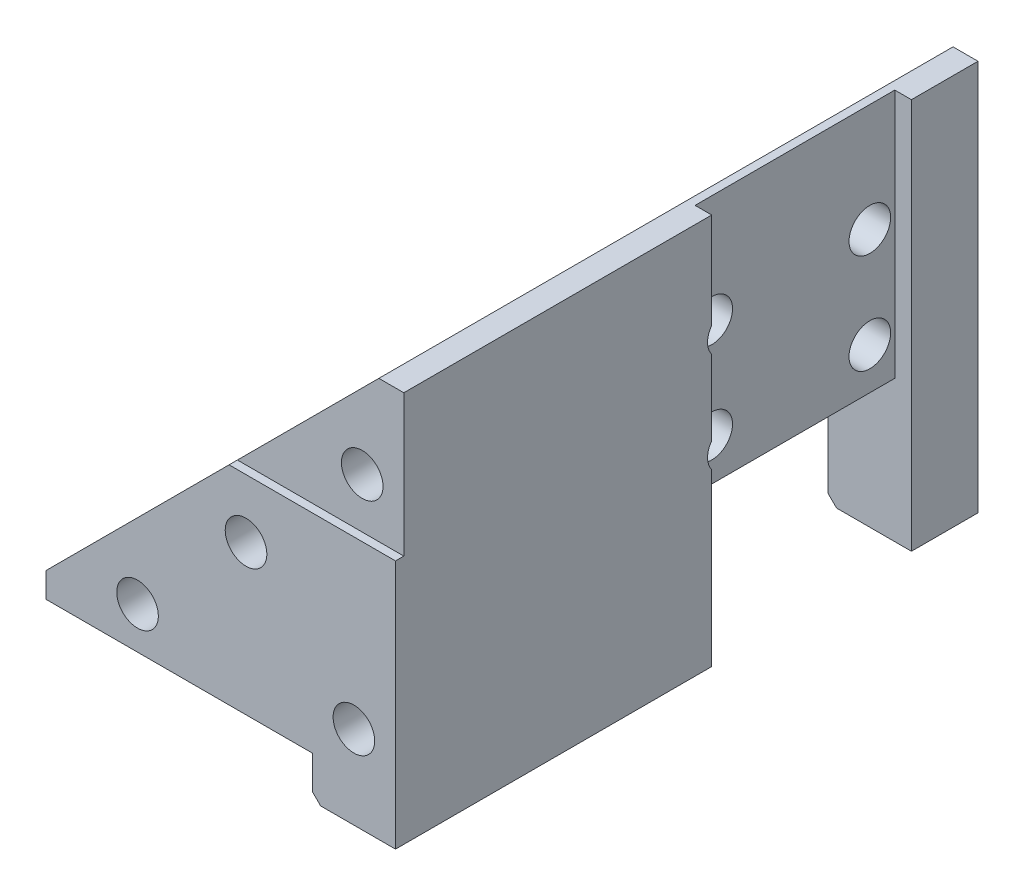
SolidWorks part; units mm, degrees
ref_plane "前视基准面" through (0, 0, 0) normal (0, 0, 1) x (1, 0, 0)
ref_plane "上视基准面" through (0, 0, 0) normal (0, 1, 0) x (1, 0, 0)
ref_plane "右视基准面" through (0, 0, 0) normal (1, 0, 0) x (0, 0, -1)
sketch "草图1" plane through (0, 0, 0) normal (0, 0, 1) x (1, 0, 0)
  line L0 (0, 0) -> (50, 0)
  line L1 (50, 0) -> (50, 50)
  line L3 (50, 50) -> (0, 0)
  dimension "D1" = 45
  dimension "D2" = 50
extrude "拉伸1" add sketch "草图1" along normal blind 70
sketch "草图2" plane through (0, 0, 70) normal (0, 0, 1) x (1, 0, 0)
  line L0 (0, 0) -> (50, 0) construction
  line L1 (40, 0) -> (-5.5322, 0)
  line L2 (40, 0) -> (40, 5)
  line L3 (40, 5) -> (-5.5322, 5)
  line L4 (-5.5322, 0) -> (-5.5322, 5)
  line L5 (50, 0) -> (50, 50) construction
  dimension "D1" = 5
  dimension "D2" = 10
extrude "切除-拉伸1" cut sketch "草图2" against normal through all
sketch "草图3" plane through (0, 5, 0) normal (0, -1, 0) x (1, 0, 0)
  line L0 (5, 0) -> (5, 70) construction
  line L1 (5, 60) -> (40, 60)
  line L2 (5, 60) -> (5, 50)
  line L3 (5, 50) -> (40, 50)
  line L4 (40, 60) -> (40, 50)
  line L5 (40, 0) -> (40, 70) construction
  line L6 (40, 70) -> (5, 70) construction
  line L7 (40, 0) -> (40, 70) construction
  line L8 (5, 40) -> (40, 40)
  line L9 (5, 40) -> (5, -6.8664)
  line L10 (5, -6.8664) -> (40, -6.8664)
  line L11 (40, 40) -> (40, -6.8664)
  dimension "D1" = 10
  dimension "D2" = 10
  dimension "D4" = 10
extrude "切除-拉伸2" cut sketch "草图3" against normal through all
sketch "草图4" plane through (0, 0, 70) normal (0, 0, 1) x (1, 0, 0)
  line L0 (5, 5) -> (8, 5)
  line L1 (40, 5) -> (5, 5) construction
  line L2 (8, 5) -> (8, 8)
  line L3 (50, 50) -> (5, 5) construction
  line L4 (8, 8) -> (5, 5)
  line L5 (50, 0) -> (50, 50) construction
  dimension "D1" = 42
extrude "切除-拉伸3" cut sketch "草图4" against normal through all
sketch "草图9" plane through (0, 0, 70) normal (0, 0, 1) x (1, 0, 0)
  line L0 (45, 36) -> (45, -4.6251) construction
  line L1 (50, 0) -> (50, 50) construction
  line L2 (40, 0) -> (50, 0) construction
  line L3 (50, 25) -> (8.9352, 25) construction
  line L4 (45, 36) -> (19, 10) construction
  line L5 (19, 10) -> (45, 10) construction
  line L6 (50, 50) -> (8, 8) construction
  circle A0 centre (45, 36) radius 2.5
  circle A1 centre (45, 10) radius 2.5
  circle A2 centre (19, 10) radius 2.5
  dimension "D2" = 5
  dimension "D1" = 5
  dimension "D3" = 10
  dimension "D4" = 26
extrude "切除-拉伸7" cut sketch "草图9" against normal up to surface (20 mm away) up to face at (24, 14.5, 50)
sketch "草图6" plane through (0, 0, 70) normal (0, 0, 1) x (1, 0, 0)
  line L0 (45, 36) -> (19, 10) construction
  line L2 (45, 10) -> (32.0363, 22.9637) construction
  circle A0 centre (32.0363, 22.9637) radius 6.5 construction
  dimension "D3" = 13
sketch "草图7" plane through (0, 0, 40) normal (0, 0, -1) x (-1, 0, 0)
  circle A0 centre (-32.0363, 22.9637) radius 2.5
  circle A1 centre (-32.0363, 22.9637) radius 6.5 construction
  dimension "D1" = 5
chamfer "倒角1" distance 1 angle 45 3 edges at (24, 5, 60) (24, 5, 50) (24, 5, 40)
sketch "草图11" plane through (0, 5, 0) normal (0, -1, 0) x (1, 0, 0)
  line L0 (40, 70) -> (8, 70) construction
  line L1 (40, 61) -> (40, 70) construction
  circle A0 centre (34, 65) radius 3.75
  dimension "D1" = 7.5
  dimension "D2" = 5
  dimension "D3" = 6
extrude "切除-拉伸10" cut sketch "草图11" against normal blind 8
sketch "草图13" plane through (0, 0, 70) normal (0, 0, 1) x (1, 0, 0)
  line L0 (50, 50) -> (47, 47)
  line L1 (50, 50) -> (8, 8) construction
  line L2 (47, 47) -> (50, 47)
  line L3 (50, 0) -> (50, 50) construction
  line L4 (50, 47) -> (50, 50)
  dimension "D1" = 3
extrude "切除-拉伸11" cut sketch "草图13" against normal through all
sketch "草图14" plane through (0, 0, 70) normal (0, 0, 1) x (1, 0, 0)
  line L0 (50, 47) -> (47, 47)
  line L1 (47, 47) -> (30, 30)
  line L2 (47, 47) -> (8, 8) construction
  line L3 (30, 30) -> (50, 30)
  line L4 (50, 0) -> (50, 47) construction
  line L5 (50, 30) -> (50, 47)
  dimension "D1" = 17
extrude "切除-拉伸12" cut sketch "草图14" against normal blind 1
sketch "草图15" plane through (40, 0, 0) normal (-1, 0, 0) x (0, 0, 1)
  line L0 (0, 0) -> (70, 0) construction
  line L1 (8, 0) -> (32, 0)
  line L2 (8, 0) -> (8, 17)
  line L3 (8, 17) -> (32, 17)
  line L4 (32, 0) -> (32, 17)
  line L5 (0, 0) -> (0, 40) construction
  dimension "D1" = 17
  dimension "D2" = 8
  dimension "D3" = 24
extrude "切除-拉伸14" cut sketch "草图15" against normal blind 10
sketch "草图16" plane through (40, 0, 0) normal (-1, 0, 0) x (0, 0, 1)
  line L0 (30, 34) -> (11, 34) construction
  line L1 (30, 22) -> (11, 22) construction
  line L2 (30, 34) -> (30, 22) construction
  line L3 (11, 34) -> (11, 22) construction
  line L4 (0, 0) -> (0, 40) construction
  line L5 (0, 0) -> (8, 0) construction
  circle A0 centre (30, 34) radius 2.5
  circle A1 centre (30, 22) radius 2.5
  circle A2 centre (11, 34) radius 2.5
  circle A3 centre (11, 22) radius 2.5
  point P10 (4, 0)
  dimension "D1" = 5
  dimension "D2" = 11
  dimension "D3" = 22
  dimension "D4" = 12
  dimension "D5" = 19
extrude "切除-拉伸15" cut sketch "草图16" against normal through all
sketch "草图17" plane through (50, 0, 0) normal (1, 0, 0) x (0, 0, -1)
  line L0 (0, 47) -> (-69, 47) construction
  line L1 (-32, 17) -> (-8, 17)
  line L2 (-32, 17) -> (-32, 47)
  line L3 (-32, 47) -> (-8, 47)
  line L4 (-8, 17) -> (-8, 47)
  line L5 (-8, 17) -> (-8, 0) construction
extrude "切除-拉伸16" cut sketch "草图17" against normal blind 2
extrude "切除-拉伸17" cut sketch "草图7" against normal through all
chamfer "倒角2" distance 1 angle 45 1 edges at (40, 0, 51)
chamfer "倒角3" distance 1 angle 45 1 edges at (40, 0, 4)
